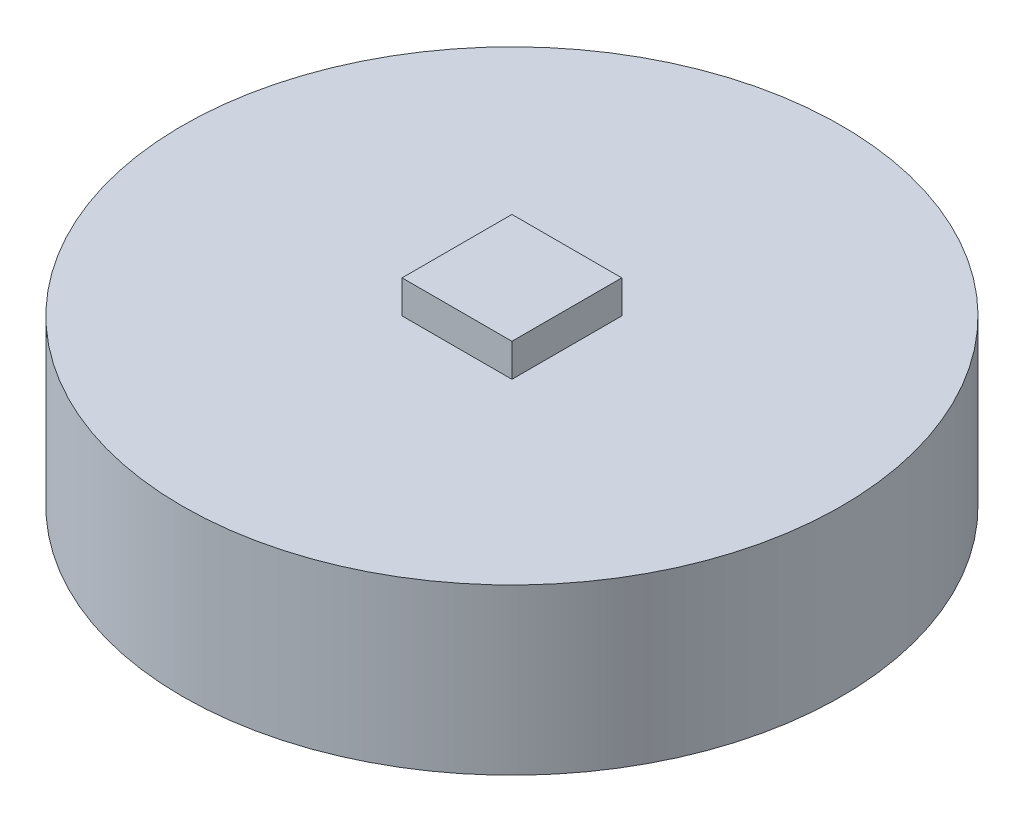
SolidWorks part; units mm, degrees
ref_plane "Front Plane" through (0, 0, 0) normal (0, 0, 1) x (1, 0, 0)
ref_plane "Top Plane" through (0, 0, 0) normal (0, 1, 0) x (1, 0, 0)
ref_plane "Right Plane" through (0, 0, 0) normal (1, 0, 0) x (0, 0, -1)
sketch "Sketch1" plane through (0, 0, 0) normal (0, 1, 0) x (1, 0, 0)
  circle A0 centre (0, 0) radius 30
  dimension "D1" = 60
extrude "Boss-Extrude1" add sketch "Sketch1" along normal blind 15
sketch "Sketch2" plane through (0, 15, 0) normal (0, 1, 0) x (1, 0, 0)
  line L1 (-5, -5) -> (5, -5)
  line L2 (-5, -5) -> (-5, 5)
  line L3 (-5, 5) -> (5, 5)
  line L4 (5, -5) -> (5, 5)
  line L5 (-5, -5) -> (5, 5) construction
  line L6 (-5, 5) -> (5, -5) construction
  point P0 (0, 0)
  dimension "D1" = 10
  dimension "D2" = 10
extrude "Boss-Extrude2" add sketch "Sketch2" along normal blind 3
sketch "Sketch3" plane through (0, 0, 0) normal (0, -1, 0) x (1, 0, 0)
  line L1 (5, 5) -> (-5, 5)
  line L2 (5, 5) -> (5, -5)
  line L3 (5, -5) -> (-5, -5)
  line L4 (-5, 5) -> (-5, -5)
  line L5 (5, 5) -> (-5, -5) construction
  line L6 (5, -5) -> (-5, 5) construction
  point P0 (0, 0)
  dimension "D1" = 10
  dimension "D2" = 10
extrude "Cut-Extrude1" cut sketch "Sketch3" against normal blind 3
